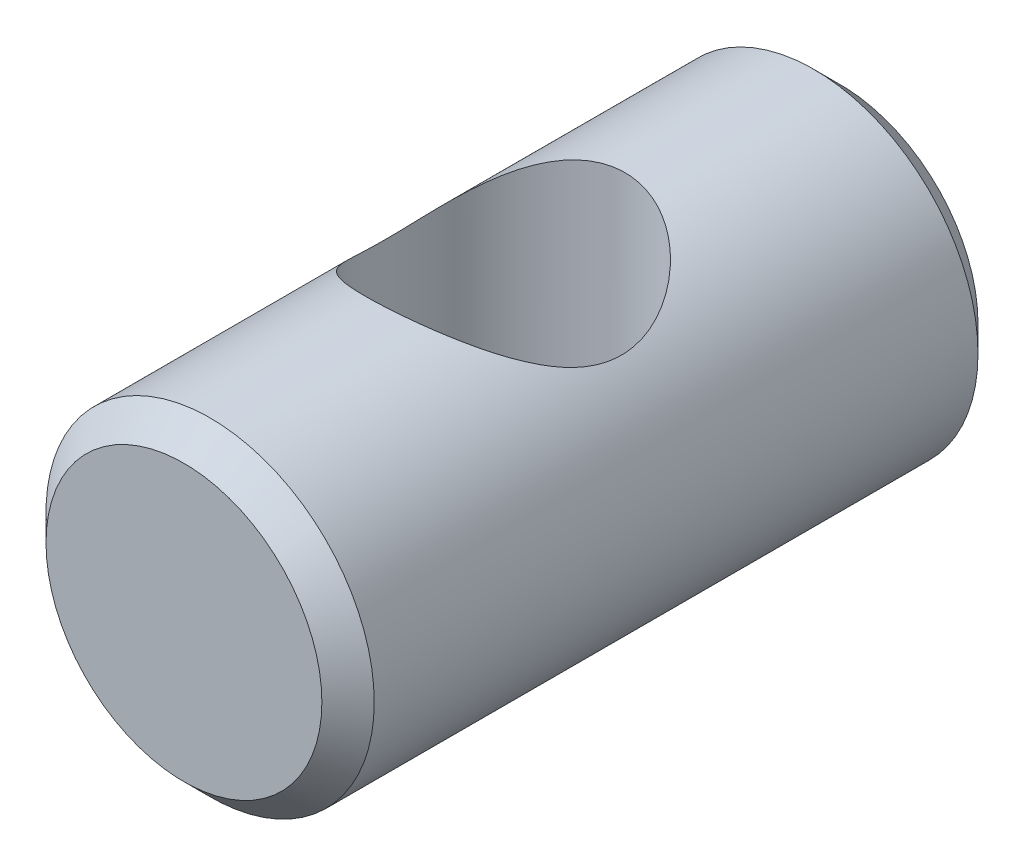
SolidWorks part; units mm, degrees
ref_plane "Front Plane" through (0, 0, 0) normal (0, 0, 1) x (1, 0, 0)
ref_plane "Top Plane" through (0, 0, 0) normal (0, 1, 0) x (1, 0, 0)
ref_plane "Right Plane" through (0, 0, 0) normal (1, 0, 0) x (0, 0, -1)
sketch "Sketch1" plane through (0, 0, 0) normal (0, 0, 1) x (1, 0, 0)
  circle A0 centre (0, 0) radius 4.765
  dimension "D1" = 9.53
extrude "Boss-Extrude1" add sketch "Sketch1" along normal mid plane 19.05
chamfer "Chamfer1" distance 0.76 angle 45 2 edges at (4.765, 0, -9.525) (4.765, 0, 9.525)
sketch "Sketch2" plane through (0, 0, 0) normal (0, 1, 0) x (1, 0, 0)
  circle A0 centre (-0.25, 0) radius 3.43
  point P3 (0, 0)
  point P4 (-0.8786, 0)
  dimension "D1" = 6.86
  dimension "D2" = 0.25
extrude "Cut-Extrude1" cut sketch "Sketch2" against normal mid plane 19.05
